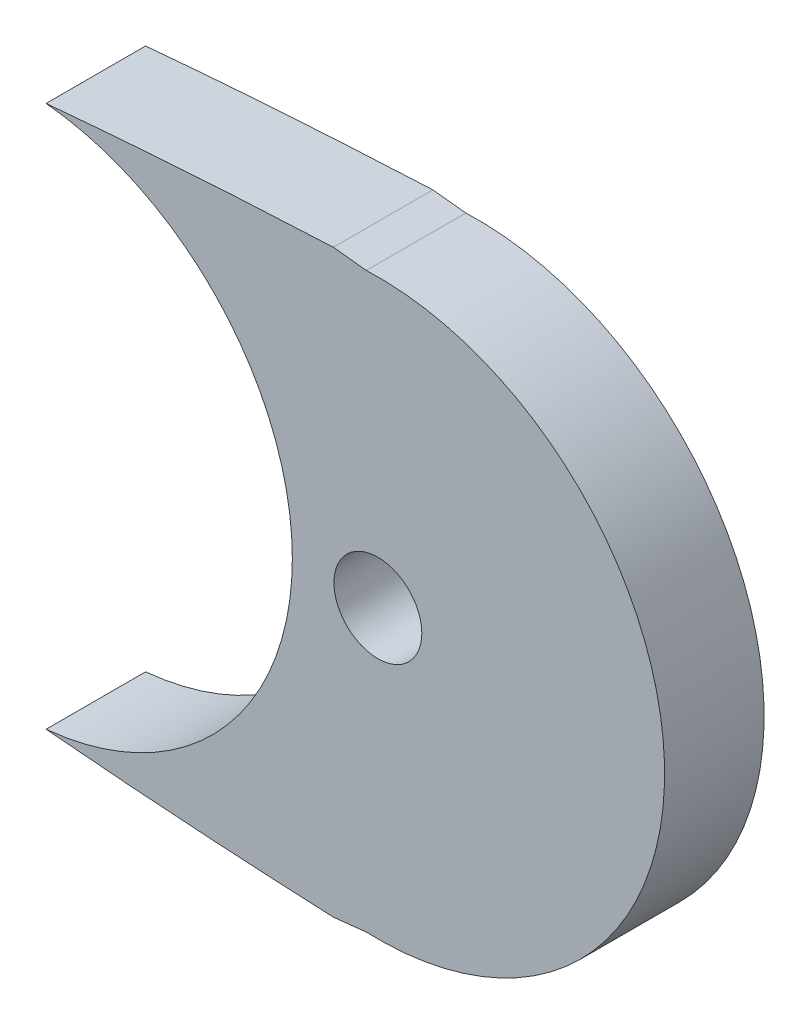
SolidWorks part; units mm, degrees
ref_plane "Front Plane" through (0, 0, 0) normal (0, 0, 1) x (1, 0, 0)
ref_plane "Top Plane" through (0, 0, 0) normal (0, 1, 0) x (1, 0, 0)
ref_plane "Right Plane" through (0, 0, 0) normal (1, 0, 0) x (0, 0, -1)
curve "Curve2"
  spline degree 3 poles (300, 0.378, 0) (299.8459, 0.3996, 0) (299.2303, 0.4859, 0) (297.8489, 0.6785, 0) (295.556, 0.9968, 0) (292.3657, 1.4334, 0) (288.2979, 1.9834, 0) (283.3772, 2.6357, 0) (277.6343, 3.3815, 0) (271.1045, 4.209, 0) (263.8281, 5.1072, 0) (255.8498, 6.0628, 0) (247.219, 7.0642, 0) (237.9888, 8.0979, 0) (228.216, 9.1511, 0) (217.9611, 10.2107, 0) (207.2872, 11.2632, 0) (196.2601, 12.2937, 0) (184.9478, 13.2887, 0) (173.4201, 14.2316, 0) (161.7479, 15.107, 0) (150.0032, 15.8986, 0) (138.2584, 16.5898, 0) (126.5858, 17.1634, 0) (115.0575, 17.6038, 0) (103.7442, 17.8968, 0) (92.7158, 18.028, 0) (82.0402, 17.9871, 0) (71.7831, 17.7661, 0) (62.0077, 17.3595, 0) (52.7741, 16.7661, 0) (44.1391, 15.9878, 0) (36.1555, 15.0306, 0) (28.872, 13.9026, 0) (22.3327, 12.6157, 0) (16.576, 11.1845, 0) (11.6345, 9.6228, 0) (7.5334, 7.9452, 0) (4.2857, 6.163, 0) (1.8965, 4.2728, 0) (0.3663, 2.2288, 0) (-0.1707, 0, 0) (0.3663, -2.2288, 0) (1.8965, -4.2728, 0) (4.2857, -6.163, 0) (7.5334, -7.9452, 0) (11.6345, -9.6228, 0) (16.576, -11.1845, 0) (22.3327, -12.6157, 0) (28.872, -13.9026, 0) (36.1555, -15.0306, 0) (44.1391, -15.9878, 0) (52.7741, -16.7661, 0) (62.0077, -17.3595, 0) (71.7831, -17.7661, 0) (82.0402, -17.9871, 0) (92.7158, -18.028, 0) (103.7442, -17.8968, 0) (115.0575, -17.6038, 0) (126.5858, -17.1634, 0) (138.2584, -16.5898, 0) (150.0032, -15.8986, 0) (161.7479, -15.107, 0) (173.4201, -14.2316, 0) (184.9478, -13.2887, 0) (196.2601, -12.2937, 0) (207.2872, -11.2632, 0) (217.9611, -10.2107, 0) (228.216, -9.1511, 0) (237.9888, -8.0979, 0) (247.219, -7.0642, 0) (255.8498, -6.0628, 0) (263.8281, -5.1072, 0) (271.1045, -4.209, 0) (277.6343, -3.3815, 0) (283.3772, -2.6357, 0) (288.2979, -1.9834, 0) (292.3657, -1.4334, 0) (295.556, -0.9968, 0) (297.8489, -0.6785, 0) (299.2303, -0.4859, 0) (299.8459, -0.3996, 0) (300, -0.378, 0) knots 0 0 0 0 0.000763 0.003048 0.006841 0.012116 0.018841 0.026973 0.03646 0.047243 0.059254 0.072417 0.086651 0.101866 0.117969 0.134858 0.152428 0.170572 0.189175 0.208122 0.227297 0.24658 0.265853 0.284997 0.303895 0.322433 0.340499 0.357984 0.374788 0.390812 0.405965 0.420162 0.433328 0.445394 0.456301 0.466004 0.474472 0.481696 0.487704 0.492583 0.496544 0.5 0.503456 0.507417 0.512296 0.518304 0.525528 0.533996 0.543699 0.554606 0.566672 0.579838 0.594035 0.609188 0.625212 0.642016 0.659501 0.677567 0.696105 0.715003 0.734147 0.75342 0.772703 0.791878 0.810825 0.829428 0.847572 0.865142 0.882031 0.898134 0.913349 0.927583 0.940746 0.952757 0.96354 0.973027 0.981159 0.987884 0.993159 0.996952 0.999237 1 1 1 1
sketch "Sketch2" plane through (0, 0, 0) normal (0, 0, 1) x (1, 0, 0)
  line L0 (0, 0) -> (300.3287, 0) construction
  line L9 (300, 0.378) -> (300, -0.378)
  line L17 (90, 18.0052) -> (90, -18.0052)
  line L20 (25.2817, 12.903) -> (25.2817, -12.903)
  line L21 (46.6322, 16.1183) -> (46.6322, -16.1183)
  line L22 (68.2099, 17.5933) -> (68.2099, -17.5933)
  line L23 (131.5031, 16.8963) -> (131.5031, -16.8963)
  line L24 (173.2123, 14.1909) -> (173.2123, -14.1909)
  line L25 (215.2898, -10.4186) -> (215.2898, 10.4186)
  line L26 (257.3103, -5.8439) -> (257.3103, 5.8439)
  arc A0 (300, -0.378) -> (300, 0.378) centre (299.947, 0) ccw
  arc A3 (45, 16.0354) -> (45, -16.0354) centre (46.6322, 0) ccw
  arc A5 (67.5, -17.5789) -> (67.5, 17.5789) centre (68.2099, 0) cw
  arc A6 (22.5, 12.5996) -> (22.5, -12.5996) centre (25.2817, 0) ccw
  arc A7 (258, -5.8031) -> (258, 5.8031) centre (257.3103, 0) cw
  arc A8 (216.3287, -10.3667) -> (216.3287, 10.3667) centre (215.2898, 0) cw
  arc A9 (174.3287, -14.147) -> (174.3287, 14.147) centre (173.2123, 0) cw
  arc A11 (132.3287, -16.8761) -> (132.3287, 16.8761) centre (131.5031, 0) cw
  arc A12 (90, -18.0052) -> (90, 18.0052) centre (89.9987, 0) cw
  arc A13 (22.5, 12.5996) -> (22.5, -12.5996) centre (25.2817, 0) cw
  arc A14 (45, 16.0354) -> (45, -16.0354) centre (46.6322, 0) cw
  arc A15 (67.5, 17.5789) -> (67.5, -17.5789) centre (68.2099, 0) cw
  arc A16 (90, -18.0052) -> (90, 18.0052) centre (90, 0) ccw
  arc A17 (132.3287, 16.8761) -> (132.3287, -16.8761) centre (131.5031, 0) cw
  arc A18 (174.3287, 14.147) -> (174.3287, -14.147) centre (173.2123, 0) cw
  arc A19 (216.3287, 10.3667) -> (216.3287, -10.3667) centre (215.2898, 0) cw
  arc A20 (257.9987, 5.8032) -> (257.9987, -5.8032) centre (257.309, 0) cw
  circle A21 centre (25.2817, 0) radius 12.903
  circle A22 centre (257.3103, 0) radius 5.8439
  circle A23 centre (25.2817, 0) radius 2.65
  circle A24 centre (8, 0) radius 2.65
  circle A25 centre (46.6322, 0) radius 2.65
  circle A26 centre (68.2099, 0) radius 2.65
  spline S0 degree 3 poles (1085.0864, 3916.8712) (453.7719, -29.1916) (376.7513, -10.3218) (297.8489, 0.6785) (295.556, 0.9968) (292.3657, 1.4334) (288.2979, 1.9834) (283.3772, 2.6357) (277.6343, 3.3815) (271.1045, 4.209) (263.8281, 5.1072) (255.8498, 6.0628) (247.219, 7.0642) (237.9888, 8.0979) (228.216, 9.1511) (217.9611, 10.2107) (207.2872, 11.2632) (196.2601, 12.2937) (184.9478, 13.2887) (173.4201, 14.2316) (161.7479, 15.107) (150.0032, 15.8986) (138.2584, 16.5898) (126.5858, 17.1634) (115.0575, 17.6038) (103.7442, 17.8968) (92.7158, 18.028) (82.0402, 17.9871) (71.7831, 17.7661) (62.0077, 17.3595) (52.7741, 16.7661) (44.1391, 15.9878) (36.1555, 15.0306) (28.872, 13.9026) (22.3327, 12.6157) (16.576, 11.1845) (11.6345, 9.6228) (7.5334, 7.9452) (4.2857, 6.163) (1.8965, 4.2728) (0.3663, 2.2288) (-0.1707, 0) (0.3663, -2.2288) (1.8965, -4.2728) (4.2857, -6.163) (7.5334, -7.9452) (11.6345, -9.6228) (16.576, -11.1845) (22.3327, -12.6157) (28.872, -13.9026) (36.1555, -15.0306) (44.1391, -15.9878) (52.7741, -16.7661) (62.0077, -17.3595) (71.7831, -17.7661) (82.0402, -17.9871) (92.7158, -18.028) (103.7442, -17.8968) (115.0575, -17.6038) (126.5858, -17.1634) (138.2584, -16.5898) (150.0032, -15.8986) (161.7479, -15.107) (173.4201, -14.2316) (184.9478, -13.2887) (196.2601, -12.2937) (207.2872, -11.2632) (217.9611, -10.2107) (228.216, -9.1511) (237.9888, -8.0979) (247.219, -7.0642) (255.8498, -6.0628) (263.8281, -5.1072) (271.1045, -4.209) (277.6343, -3.3815) (283.3772, -2.6357) (288.2979, -1.9834) (292.3657, -1.4334) (295.556, -0.9968) (297.8489, -0.6785) (376.7507, 10.3217) (453.7706, 29.1913) (1085.0706, -3916.7726) knots -0.383871 -0.383871 -0.383871 -0.383871 0.000763 0.003048 0.006841 0.012116 0.018841 0.026973 0.03646 0.047243 0.059254 0.072417 0.086651 0.101866 0.117969 0.134858 0.152428 0.170572 0.189175 0.208122 0.227297 0.24658 0.265853 0.284997 0.303895 0.322433 0.340499 0.357984 0.374788 0.390812 0.405965 0.420162 0.433328 0.445394 0.456301 0.466004 0.474472 0.481696 0.487704 0.492583 0.496544 0.5 0.503456 0.507417 0.512296 0.518304 0.525528 0.533996 0.543699 0.554606 0.566672 0.579838 0.594035 0.609188 0.625212 0.642016 0.659501 0.677567 0.696105 0.715003 0.734147 0.75342 0.772703 0.791878 0.810825 0.829428 0.847572 0.865142 0.882031 0.898134 0.913349 0.927583 0.940746 0.952757 0.96354 0.973027 0.981159 0.987884 0.993159 0.996952 0.999237 1.383868 1.383868 1.383868 1.383868 only from (300, 0.378) to (300, -0.378) construction
  spline S1 degree 3 poles (300, 0.378) (299.8459, 0.3996) (299.2303, 0.4859) (297.8489, 0.6785) (295.556, 0.9968) (292.3657, 1.4334) (288.2979, 1.9834) (283.3772, 2.6357) (277.6343, 3.3815) (271.1045, 4.209) (263.8281, 5.1072) (255.8498, 6.0628) (247.219, 7.0642) (237.9888, 8.0979) (228.216, 9.1511) (217.9611, 10.2107) (207.2872, 11.2632) (196.2601, 12.2937) (184.9478, 13.2887) (173.4201, 14.2316) (161.7479, 15.107) (150.0032, 15.8986) (138.2584, 16.5898) (126.5858, 17.1634) (115.0575, 17.6038) (103.7442, 17.8968) (92.7158, 18.028) (82.0402, 17.9871) (71.7831, 17.7661) (62.0077, 17.3595) (52.7741, 16.7661) (44.1391, 15.9878) (36.1555, 15.0306) (28.872, 13.9026) (22.3327, 12.6157) (16.576, 11.1845) (11.6345, 9.6228) (7.5334, 7.9452) (4.2857, 6.163) (1.8965, 4.2728) (0.3663, 2.2288) (-0.1707, 0) (0.3663, -2.2288) (1.8965, -4.2728) (4.2857, -6.163) (7.5334, -7.9452) (11.6345, -9.6228) (16.576, -11.1845) (22.3327, -12.6157) (28.872, -13.9026) (36.1555, -15.0306) (44.1391, -15.9878) (52.7741, -16.7661) (62.0077, -17.3595) (71.7831, -17.7661) (82.0402, -17.9871) (92.7158, -18.028) (103.7442, -17.8968) (115.0575, -17.6038) (126.5858, -17.1634) (138.2584, -16.5898) (150.0032, -15.8986) (161.7479, -15.107) (173.4201, -14.2316) (184.9478, -13.2887) (196.2601, -12.2937) (207.2872, -11.2632) (217.9611, -10.2107) (228.216, -9.1511) (237.9888, -8.0979) (247.219, -7.0642) (255.8498, -6.0628) (263.8281, -5.1072) (271.1045, -4.209) (277.6343, -3.3815) (283.3772, -2.6357) (288.2979, -1.9834) (292.3657, -1.4334) (295.556, -0.9968) (297.8489, -0.6785) (299.2303, -0.4859) (299.8459, -0.3996) (300, -0.378) knots 0 0 0 0 0.000763 0.003048 0.006841 0.012116 0.018841 0.026973 0.03646 0.047243 0.059254 0.072417 0.086651 0.101866 0.117969 0.134858 0.152428 0.170572 0.189175 0.208122 0.227297 0.24658 0.265853 0.284997 0.303895 0.322433 0.340499 0.357984 0.374788 0.390812 0.405965 0.420162 0.433328 0.445394 0.456301 0.466004 0.474472 0.481696 0.487704 0.492583 0.496544 0.5 0.503456 0.507417 0.512296 0.518304 0.525528 0.533996 0.543699 0.554606 0.566672 0.579838 0.594035 0.609188 0.625212 0.642016 0.659501 0.677567 0.696105 0.715003 0.734147 0.75342 0.772703 0.791878 0.810825 0.829428 0.847572 0.865142 0.882031 0.898134 0.913349 0.927583 0.940746 0.952757 0.96354 0.973027 0.981159 0.987884 0.993159 0.996952 0.999237 1 1 1 1
  point P47 (215.2898, 0)
  point P58 (257.3103, 0)
  point P61 (12.3787, 0)
  point P62 (62.7505, 0)
  dimension "D11" = 5.3
  dimension "D14" = 5.3
  dimension "D12" = 5.3
  dimension "D15" = 5.3
  dimension "D1" = 300.3287
  dimension "D2" = 89.9987
  dimension "D3" = 68.2099
  dimension "D4" = 46.6322
  dimension "D5" = 25.2817
  dimension "D6" = 168.8256
  dimension "D7" = 127.1164
  dimension "D8" = 85.0389
  dimension "D9" = 43.0184
  dimension "D10" = 50.3718
  dimension "D13" = 8
extrude "Boss-Extrude4" add sketch "Sketch2" along normal blind 6 contours A5 S1 A14 | A14 L0 L22 A15 A5 | L0 A14 A5 A15 L22 | A14 S1 A5 | L22 L0 A12 A15 | A12 L0 A15 | L0 L22 A15 A12 | L0 A12 A15
sketch "Sketch4" plane through (0, 0, 6) normal (0, 0, 1) x (1, 0, 0)
  line L0 (67.5121, 17.2792) -> (65.5273, 17.495)
  line L1 (67.5121, -17.2792) -> (65.5273, -17.495)
  arc A0 (67.5121, -17.2792) -> (67.5121, 17.2792) centre (68.2099, 0) ccw
  arc A1 (48.1975, -16.3435) -> (48.1975, 16.3435) centre (46.6322, 0) ccw
  arc A2 (67.5, -17.5789) -> (67.5, 17.5789) centre (68.2099, 0) ccw
  arc A3 (45, -16.0354) -> (45, 16.0354) centre (46.6322, 0) ccw
  arc A4 (67.5, -17.5789) -> (67.5, 17.5789) centre (68.2099, 0) ccw
  arc A5 (45, -16.0354) -> (45, 16.0354) centre (46.6322, 0) ccw
  arc A6 (44.9696, -16.3339) -> (44.9696, 16.3339) centre (46.6322, 0) ccw construction
  spline S2 degree 3 poles (59.5053, 2951.8518) (-322.5437, 175.1344) (-138.2485, -4.4902) (336.8173, -35.0199) (632.6179, 228.687) (327.0236, -2933.9096) knots -0.358856 -0.358856 -0.358856 -0.358856 0.594035 0.609188 1.975639 1.975639 1.975639 1.975639 only from (45, -16.0354) to (67.5, -17.5789)
  spline S3 degree 3 poles (327.0289, 2933.8547) (632.6145, -228.684) (336.8157, 35.0198) (-138.2512, 4.49) (-322.5488, -175.1394) (59.5214, -2951.9686) knots -0.975631 -0.975631 -0.975631 -0.975631 0.390812 0.405965 1.358869 1.358869 1.358869 1.358869 only from (67.5, 17.5789) to (45, 16.0354)
  spline S4 degree 3 poles (45, -16.0354) (47.5247, -16.2924) (53.1306, -16.789) (60.6344, -17.2712) (65.6102, -17.5026) (67.5, -17.5789) knots 0.581589 0.581589 0.581589 0.581589 0.594035 0.609188 0.618464 0.618464 0.618464 0.618464
  spline S5 degree 3 poles (67.5, 17.5789) (65.6102, 17.5026) (60.6344, 17.2712) (53.1306, 16.789) (47.5247, 16.2924) (45, 16.0354) knots 0.381536 0.381536 0.381536 0.381536 0.390812 0.405965 0.418411 0.418411 0.418411 0.418411
  spline M5 degree 3 poles (300, 0.378) (299.8459, 0.3996) (299.2303, 0.4859) (297.8489, 0.6785) (295.556, 0.9968) (292.3657, 1.4334) (288.2979, 1.9834) (283.3772, 2.6357) (277.6343, 3.3815) (271.1045, 4.209) (263.8281, 5.1072) (255.8498, 6.0628) (247.219, 7.0642) (237.9888, 8.0979) (228.216, 9.1511) (217.9611, 10.2107) (207.2872, 11.2632) (196.2601, 12.2937) (184.9478, 13.2887) (173.4201, 14.2316) (161.7479, 15.107) (150.0032, 15.8986) (138.2584, 16.5898) (126.5858, 17.1634) (115.0575, 17.6038) (103.7442, 17.8968) (92.7158, 18.028) (82.0402, 17.9871) (71.7831, 17.7661) (62.0077, 17.3595) (52.7741, 16.7661) (44.1391, 15.9878) (36.1555, 15.0306) (28.872, 13.9026) (22.3327, 12.6157) (16.576, 11.1845) (11.6345, 9.6228) (7.5334, 7.9452) (4.2857, 6.163) (1.8965, 4.2728) (0.3663, 2.2288) (-0.1707, 0) (0.3663, -2.2288) (1.8965, -4.2728) (4.2857, -6.163) (7.5334, -7.9452) (11.6345, -9.6228) (16.576, -11.1845) (22.3327, -12.6157) (28.872, -13.9026) (36.1555, -15.0306) (44.1391, -15.9878) (52.7741, -16.7661) (62.0077, -17.3595) (71.7831, -17.7661) (82.0402, -17.9871) (92.7158, -18.028) (103.7442, -17.8968) (115.0575, -17.6038) (126.5858, -17.1634) (138.2584, -16.5898) (150.0032, -15.8986) (161.7479, -15.107) (173.4201, -14.2316) (184.9478, -13.2887) (196.2601, -12.2937) (207.2872, -11.2632) (217.9611, -10.2107) (228.216, -9.1511) (237.9888, -8.0979) (247.219, -7.0642) (255.8498, -6.0628) (263.8281, -5.1072) (271.1045, -4.209) (277.6343, -3.3815) (283.3772, -2.6357) (288.2979, -1.9834) (292.3657, -1.4334) (295.556, -0.9968) (297.8489, -0.6785) (299.2303, -0.4859) (299.8459, -0.3996) (300, -0.378) knots 0 0 0 0 0.000763 0.003048 0.006841 0.012116 0.018841 0.026973 0.03646 0.047243 0.059254 0.072417 0.086651 0.101866 0.117969 0.134858 0.152428 0.170572 0.189175 0.208122 0.227297 0.24658 0.265853 0.284997 0.303895 0.322433 0.340499 0.357984 0.374788 0.390812 0.405965 0.420162 0.433328 0.445394 0.456301 0.466004 0.474472 0.481696 0.487704 0.492583 0.496544 0.5 0.503456 0.507417 0.512296 0.518304 0.525528 0.533996 0.543699 0.554606 0.566672 0.579838 0.594035 0.609188 0.625212 0.642016 0.659501 0.677567 0.696105 0.715003 0.734147 0.75342 0.772703 0.791878 0.810825 0.829428 0.847572 0.865142 0.882031 0.898134 0.913349 0.927583 0.940746 0.952757 0.96354 0.973027 0.981159 0.987884 0.993159 0.996952 0.999237 1 1 1 1 only from (45, -16.0354) to (67.5, -17.5789)
  arc M6 (67.5, -17.5789) -> (67.5, 17.5789) centre (68.2099, 0) ccw
  spline M7 degree 3 poles (300, 0.378) (299.8459, 0.3996) (299.2303, 0.4859) (297.8489, 0.6785) (295.556, 0.9968) (292.3657, 1.4334) (288.2979, 1.9834) (283.3772, 2.6357) (277.6343, 3.3815) (271.1045, 4.209) (263.8281, 5.1072) (255.8498, 6.0628) (247.219, 7.0642) (237.9888, 8.0979) (228.216, 9.1511) (217.9611, 10.2107) (207.2872, 11.2632) (196.2601, 12.2937) (184.9478, 13.2887) (173.4201, 14.2316) (161.7479, 15.107) (150.0032, 15.8986) (138.2584, 16.5898) (126.5858, 17.1634) (115.0575, 17.6038) (103.7442, 17.8968) (92.7158, 18.028) (82.0402, 17.9871) (71.7831, 17.7661) (62.0077, 17.3595) (52.7741, 16.7661) (44.1391, 15.9878) (36.1555, 15.0306) (28.872, 13.9026) (22.3327, 12.6157) (16.576, 11.1845) (11.6345, 9.6228) (7.5334, 7.9452) (4.2857, 6.163) (1.8965, 4.2728) (0.3663, 2.2288) (-0.1707, 0) (0.3663, -2.2288) (1.8965, -4.2728) (4.2857, -6.163) (7.5334, -7.9452) (11.6345, -9.6228) (16.576, -11.1845) (22.3327, -12.6157) (28.872, -13.9026) (36.1555, -15.0306) (44.1391, -15.9878) (52.7741, -16.7661) (62.0077, -17.3595) (71.7831, -17.7661) (82.0402, -17.9871) (92.7158, -18.028) (103.7442, -17.8968) (115.0575, -17.6038) (126.5858, -17.1634) (138.2584, -16.5898) (150.0032, -15.8986) (161.7479, -15.107) (173.4201, -14.2316) (184.9478, -13.2887) (196.2601, -12.2937) (207.2872, -11.2632) (217.9611, -10.2107) (228.216, -9.1511) (237.9888, -8.0979) (247.219, -7.0642) (255.8498, -6.0628) (263.8281, -5.1072) (271.1045, -4.209) (277.6343, -3.3815) (283.3772, -2.6357) (288.2979, -1.9834) (292.3657, -1.4334) (295.556, -0.9968) (297.8489, -0.6785) (299.2303, -0.4859) (299.8459, -0.3996) (300, -0.378) knots 0 0 0 0 0.000763 0.003048 0.006841 0.012116 0.018841 0.026973 0.03646 0.047243 0.059254 0.072417 0.086651 0.101866 0.117969 0.134858 0.152428 0.170572 0.189175 0.208122 0.227297 0.24658 0.265853 0.284997 0.303895 0.322433 0.340499 0.357984 0.374788 0.390812 0.405965 0.420162 0.433328 0.445394 0.456301 0.466004 0.474472 0.481696 0.487704 0.492583 0.496544 0.5 0.503456 0.507417 0.512296 0.518304 0.525528 0.533996 0.543699 0.554606 0.566672 0.579838 0.594035 0.609188 0.625212 0.642016 0.659501 0.677567 0.696105 0.715003 0.734147 0.75342 0.772703 0.791878 0.810825 0.829428 0.847572 0.865142 0.882031 0.898134 0.913349 0.927583 0.940746 0.952757 0.96354 0.973027 0.981159 0.987884 0.993159 0.996952 0.999237 1 1 1 1 only from (67.5, 17.5789) to (45, 16.0354)
  arc M8 (45, 16.0354) -> (45, -16.0354) centre (46.6322, 0) cw
  dimension "D1" = 0
  dimension "D2" = 0.3
  dimension "D3" = 0.3
extrude "Cut-Extrude2" cut sketch "Sketch4" against normal through all contours A0 L1 L0 M5 M6 M7 | A1 M5 M7 M8
